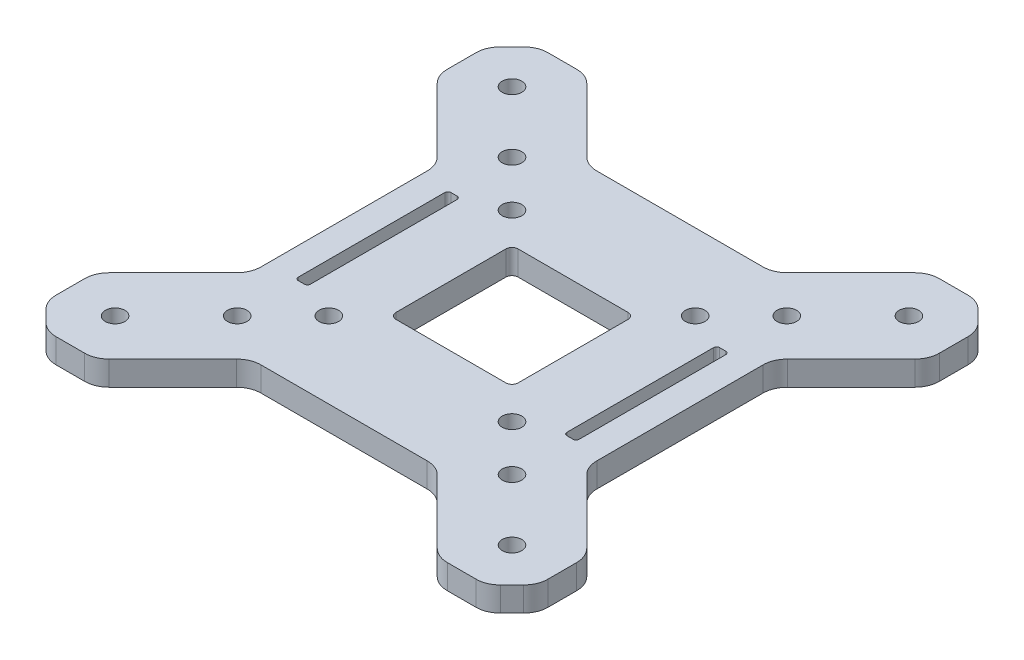
SolidWorks part; units mm, degrees
ref_plane "Front Plane" through (0, 0, 0) normal (0, 0, 1) x (1, 0, 0)
ref_plane "Top Plane" through (0, 0, 0) normal (0, 1, 0) x (1, 0, 0)
ref_plane "Right Plane" through (0, 0, 0) normal (1, 0, 0) x (0, 0, -1)
sketch "Sketch1" plane through (0, 0, 0) normal (0, 1, 0) x (1, 0, 0)
  line L0 (0, 0) -> (79.0685, 79.0685)
  line L1 (-15, 15) -> (15, 15)
  line L2 (-15, 15) -> (-15, -15)
  line L3 (-15, -15) -> (15, -15)
  line L4 (15, 15) -> (15, -15)
  line L5 (-15, 15) -> (15, -15) construction
  line L6 (-15, -15) -> (15, 15) construction
  line L7 (-22.5, 22.5) -> (22.5, 22.5)
  line L8 (-22.5, 22.5) -> (-22.5, -22.5)
  line L9 (-22.5, -22.5) -> (22.5, -22.5)
  line L10 (22.5, 22.5) -> (22.5, -22.5)
  line L11 (-22.5, 22.5) -> (22.5, -22.5) construction
  line L12 (-22.5, -22.5) -> (22.5, 22.5) construction
  line L13 (0, 0) -> (79.0685, -79.0685)
  line L14 (0, 0) -> (-79.0685, -79.0685)
  line L15 (0, 0) -> (-79.0685, 79.0685)
  line L16 (-32.5, 32.5) -> (-38.1569, 38.1569)
  line L17 (-32.5, 32.5) -> (32.5, 32.5)
  line L18 (-32.5, 32.5) -> (-32.5, -32.5)
  line L19 (-32.5, -32.5) -> (32.5, -32.5)
  line L20 (32.5, 32.5) -> (32.5, -32.5)
  line L21 (-32.5, 32.5) -> (32.5, -32.5) construction
  line L22 (-32.5, -32.5) -> (32.5, 32.5) construction
  line L23 (-27.5, 27.5) -> (27.5, 27.5)
  line L24 (-27.5, 27.5) -> (-27.5, -27.5)
  line L25 (-27.5, -27.5) -> (27.5, -27.5)
  line L26 (27.5, 27.5) -> (27.5, -27.5)
  line L27 (-27.5, 27.5) -> (27.5, -27.5) construction
  line L28 (-27.5, -27.5) -> (27.5, 27.5) construction
  line L29 (-36.0355, 40.2782) -> (-40.2782, 36.0355)
  line L30 (-40.2782, 36.0355) -> (-40.2782, 28.0355)
  line L31 (-40.2782, 28.0355) -> (-22.5, 10.2574)
  line L32 (-28.0355, 40.2782) -> (-10.2574, 22.5)
  line L33 (-36.0355, 40.2782) -> (-28.0355, 40.2782)
  line L34 (40.2782, 36.0355) -> (40.2782, 28.0355)
  line L35 (40.2782, 28.0355) -> (22.5, 10.2574)
  line L36 (40.2782, 36.0355) -> (36.0355, 40.2782)
  line L37 (36.0355, 40.2782) -> (28.0355, 40.2782)
  line L38 (28.0355, 40.2782) -> (10.2574, 22.5)
  line L39 (36.0355, -40.2782) -> (28.0355, -40.2782)
  line L40 (28.0355, -40.2782) -> (10.2574, -22.5)
  line L41 (36.0355, -40.2782) -> (40.2782, -36.0355)
  line L42 (40.2782, -36.0355) -> (40.2782, -28.0355)
  line L43 (40.2782, -28.0355) -> (22.5, -10.2574)
  line L44 (-40.2782, -36.0355) -> (-40.2782, -28.0355)
  line L45 (-40.2782, -28.0355) -> (-22.5, -10.2574)
  line L46 (-40.2782, -36.0355) -> (-36.0355, -40.2782)
  line L47 (-36.0355, -40.2782) -> (-28.0355, -40.2782)
  line L48 (-28.0355, -40.2782) -> (-10.2574, -22.5)
  circle A0 centre (79.0685, 79.0685) radius 72.5
  circle A1 centre (79.0685, -79.0685) radius 72.5
  circle A2 centre (-79.0685, -79.0685) radius 72.5
  circle A3 centre (-79.0685, 79.0685) radius 72.5
  circle A4 centre (-22.5, 22.5) radius 1.6
  circle A5 centre (-15, 15) radius 1.6
  circle A6 centre (22.5, 22.5) radius 1.6
  circle A7 centre (15, 15) radius 1.6
  circle A8 centre (22.5, -22.5) radius 1.6
  circle A9 centre (15, -15) radius 1.6
  circle A10 centre (-22.5, -22.5) radius 1.6
  circle A11 centre (-15, -15) radius 1.6
  circle A12 centre (-32.5, 32.5) radius 1.6
  circle A13 centre (32.5, 32.5) radius 1.6
  circle A14 centre (32.5, -32.5) radius 1.6
  circle A15 centre (-32.5, -32.5) radius 1.6
  point P0 (0, 0)
  point P6 (0, 0)
  point P23 (0, 0)
  point P38 (0, 0)
  point P50 (0, 0)
  point P80 (0, 0)
  dimension "D3" = 145
  dimension "D6" = 3.2
  dimension "D7" = 3.2
  dimension "D10" = 3.2
  dimension "D1" = 30
  dimension "D2" = 45
  dimension "D4" = 80
  dimension "D9" = 65
  dimension "D12" = 55
  dimension "D13" = 3
  dimension "D14" = 8
  dimension "D15" = 8
  dimension "D5" = 4
  dimension "D8" = 4
  dimension "D11" = 4
  dimension "D16" = 4
extrude "Boss-Extrude1" add sketch "Sketch1" along normal blind 4 contours A15 L18 A2 L45 L44 L46 L14 | A15 L14 L46 L47 L48 A2 L19 | A2 L18 L45 | A2 L48 L19 | A2 L19 L48 L25 L14 | A2 L14 L24 L45 L18 | A15 L14 A2 L18 | A15 L19 A2 L14 | A10 L8 L45 L24 L14 | A10 L14 L25 L48 L9 | A11 L2 A5 L15 A4 L8 A10 L14 | A11 L14 A10 L9 A8 L13 A9 L3 | L24 L45 L8 L31 | L48 L25 L40 L9 | A8 L9 L40 L25 L13 | A8 L13 L26 L43 L10 | A9 L13 A8 L10 A6 L0 A7 L4 | L43 L26 L35 L10 | A1 L20 L43 L26 L13 | A1 L13 L25 L40 L19 | A14 L13 A1 L19 | A14 L20 A1 L13 | A14 L19 A1 L40 L39 L41 L13 | A1 L19 L40 | A1 L43 L20 | A14 L13 L41 L42 L43 A1 L20 | A11 L3 A9 L13 L14 | A11 L14 L15 A5 L2 | A7 L1 A5 L15 L0 | A9 L4 A7 L0 L13 | A7 L0 A6 L7 A4 L15 A5 L1 | L38 L23 L32 L7 | A4 L7 L32 L23 L15 | A6 L0 L23 L38 L7 | A6 L10 L35 L26 L0 | A0 L0 L26 L35 L20 | A0 L17 L38 L23 L0 | A3 L18 L31 L24 L15 | A12 L15 A3 L17 | A4 L15 L24 L31 L8 | A3 L15 L23 L32 L17 | A12 L18 A3 L15 | A12 L16 L29 L30 L31 A3 L18 | A12 L17 A3 L32 L33 L29 L16 | A3 L17 L32 | A3 L31 L18 | A13 L17 A0 L0 | A13 L0 L36 L37 L38 A0 L17 | A0 L38 L17 | A0 L20 L35 | A13 L20 A0 L35 L34 L36 L0 | A13 L0 A0 L20
fillet "Fillet1" radius 4 24 edges at (28.0355, 2, 40.2782) (-28.0355, 2, 40.2782) (-36.0355, 2, 40.2782) (-40.2782, 2, 36.0355) (-40.2782, 2, 28.0355) (-27.5, 2, 15.2574) (-27.5, 2, -15.2574) (-40.2782, 2, -28.0355) (-40.2782, 2, -36.0355) (-36.0355, 2, -40.2782) (-28.0355, 2, -40.2782) (-15.2574, 2, -27.5) (15.2574, 2, -27.5) (28.0355, 2, -40.2782) (36.0355, 2, -40.2782) (40.2782, 2, -36.0355) (40.2782, 2, -28.0355) (27.5, 2, -15.2574) (27.5, 2, 15.2574) (40.2782, 2, 28.0355) (40.2782, 2, 36.0355) (36.0355, 2, 40.2782) (15.2574, 2, 27.5) (-15.2574, 2, 27.5)
sketch "Sketch2" plane through (0, 4, 0) normal (0, 1, 0) x (1, 0, 0)
  line L0 (0, 0) -> (-22, 0)
  line L1 (-10, 10) -> (10, 10)
  line L2 (-10, 10) -> (-10, -10)
  line L3 (-10, -10) -> (10, -10)
  line L4 (10, 10) -> (10, -10)
  line L5 (-10, 10) -> (10, -10) construction
  line L6 (-10, -10) -> (10, 10) construction
  line L7 (0, 0) -> (0, -10)
  line L8 (-23, 12.5) -> (-21, 12.5)
  line L9 (-23, 12.5) -> (-23, -12.5)
  line L10 (-23, -12.5) -> (-21, -12.5)
  line L11 (-21, 12.5) -> (-21, -12.5)
  line L12 (-23, 12.5) -> (-21, -12.5) construction
  line L13 (-23, -12.5) -> (-21, 12.5) construction
  line L14 (23, -12.5) -> (21, -12.5)
  line L15 (21, 12.5) -> (21, -12.5)
  line L16 (23, 12.5) -> (21, 12.5)
  line L17 (23, 12.5) -> (23, -12.5)
  point P0 (0, 0)
  dimension "D1" = 20
  dimension "D2" = 2
  dimension "D3" = 25
  dimension "D4" = 22
extrude "Cut-Extrude1" cut sketch "Sketch2" against normal blind 4
fillet "Fillet2" radius 1 4 edges at (10, 2, -10) (10, 2, 10) (-10, 2, 10) (-10, 2, -10)
fillet "Fillet3" radius 0.5 4 edges at (-21, 2, 12.5) (-23, 2, 12.5) (-21, 2, -12.5) (-23, 2, -12.5)
fillet "Fillet4" radius 0.5 4 edges at (23, 2, 12.5) (21, 2, 12.5) (23, 2, -12.5) (21, 2, -12.5)
